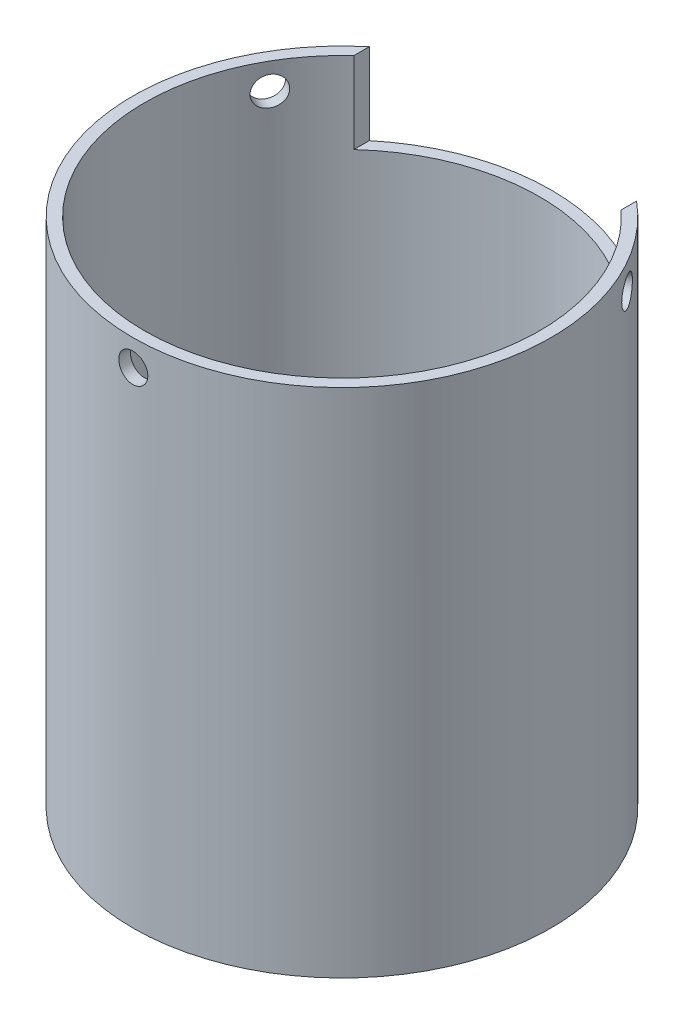
SolidWorks part; units mm, degrees
ref_plane "Front Plane" through (0, 0, 0) normal (0, 0, 1) x (1, 0, 0)
ref_plane "Top Plane" through (0, 0, 0) normal (0, 1, 0) x (1, 0, 0)
ref_plane "Right Plane" through (0, 0, 0) normal (1, 0, 0) x (0, 0, -1)
sketch "Sketch1" plane through (0, 0, 0) normal (0, 1, 0) x (1, 0, 0)
  circle A0 centre (0, 0) radius 18
  dimension "D1" = 36
extrude "Boss-Extrude1" add sketch "Sketch1" along normal blind 44
sketch "Sketch3" plane through (0, 44, 0) normal (0, 1, 0) x (1, 0, 0)
  circle A0 centre (0, 0) radius 17
  circle A1 centre (0, 0) radius 18 construction
  dimension "D1" = 1
extrude "Cut-Extrude2" cut sketch "Sketch3" against normal through all contours A0
sketch "Sketch11" plane through (0, 44, 0) normal (0, 1, 0) x (1, 0, 0)
  line L1 (-11.5, 21.8785) -> (11.5, 21.8785)
  line L2 (-11.5, 21.8785) -> (-11.5, 6.2369)
  line L3 (-11.5, 6.2369) -> (11.5, 6.2369)
  line L4 (11.5, 21.8785) -> (11.5, 6.2369)
  dimension "D1" = 23
extrude "Cut-Extrude4" cut sketch "Sketch11" against normal blind 7 contours L1 L4 L3 L2
sketch "Sketch13" plane through (0, 0, 0) normal (0, 0, 1) x (1, 0, 0)
  line L0 (18, 44) -> (-18, 44) construction
  circle A0 centre (0, 41.75) radius 1.25
  point P4 (0, 44)
  dimension "D1" = 2.5
  dimension "D3" = 2.25
  dimension "D2" = 0
extrude "Cut-Extrude5" cut sketch "Sketch13" along normal blind 20 contours A0
pattern_circular "CirPattern1" count 3 every 120 about axis through (0, 0, 0) along (0, 1, 0) of "Cut-Extrude5"
